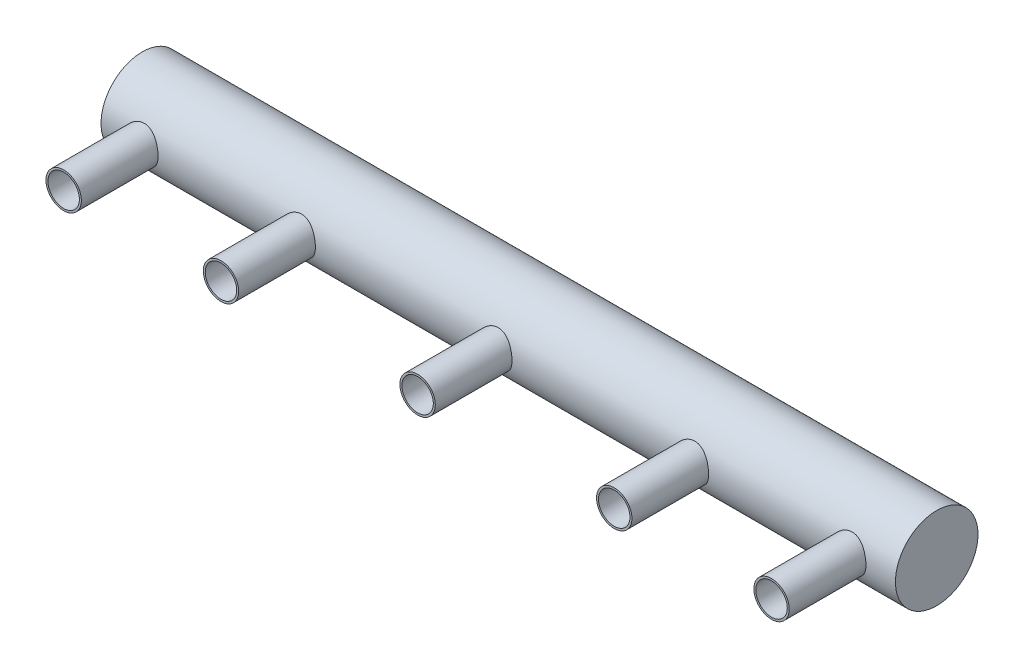
SolidWorks part; units mm, degrees
ref_plane "Front Plane" through (0, 0, 0) normal (0, 0, 1) x (1, 0, 0)
ref_plane "Top Plane" through (0, 0, 0) normal (0, 1, 0) x (1, 0, 0)
ref_plane "Right Plane" through (0, 0, 0) normal (1, 0, 0) x (0, 0, -1)
sketch "Sketch1" plane through (0, 0, 0) normal (1, 0, 0) x (0, 0, -1)
  circle A0 centre (0, 0) radius 50
  circle A1 centre (0, 0) radius 52.5
  dimension "D1" = 100
  dimension "D2" = 105
extrude "Boss-Extrude2" add sketch "Sketch1" along normal mid plane 1000 contours A0 | A1
sketch "Sketch2" plane through (0, 0, 0) normal (0, 0, 1) x (1, 0, 0)
  line L1 (57.75, 0) -> (-57.75, 0) construction
  circle A0 centre (-450, 0) radius 20
  circle A1 centre (-450, 0) radius 22.5
  circle A2 centre (450, 0) radius 20
  circle A3 centre (450, 0) radius 22.5
  circle A4 centre (-250, 0) radius 20
  circle A5 centre (-250, 0) radius 22.5
  circle A6 centre (250, 0) radius 20
  circle A7 centre (250, 0) radius 22.5
  circle A8 centre (0, 0) radius 20
  circle A9 centre (0, 0) radius 22.5
  dimension "D3" = 40
  dimension "D4" = 45
  dimension "D5" = 40
  dimension "D6" = 45
  dimension "D9" = 40
  dimension "D10" = 45
  dimension "D11" = 40
  dimension "D12" = 45
  dimension "D13" = 40
  dimension "D14" = 45
  dimension "D1" = 450
  dimension "D2" = 450
  dimension "D7" = 250
  dimension "D8" = 250
extrude "Boss-Extrude3" add sketch "Sketch2" along normal blind 150
sketch "Sketch3" plane through (0, 0, 150) normal (0, 0, 1) x (1, 0, 0)
  circle A0 centre (-450, 0) radius 20
  circle A1 centre (-250, 0) radius 20
  circle A2 centre (0, 0) radius 20
  circle A3 centre (250, 0) radius 20
  circle A4 centre (450, 0) radius 20
extrude "Cut-Extrude1" cut sketch "Sketch3" against normal blind 150
sketch "Sketch4" plane through (-500, 0, 0) normal (-1, 0, 0) x (0, 0, 1)
  circle A0 centre (0, 0) radius 50
extrude "Cut-Extrude2" cut sketch "Sketch4" against normal through all
sketch "Sketch5" plane through (500, 0, 0) normal (1, 0, 0) x (0, 0, -1)
  circle A0 centre (0, 0) radius 52.5
extrude "Boss-Extrude4" add sketch "Sketch5" along normal blind 10
